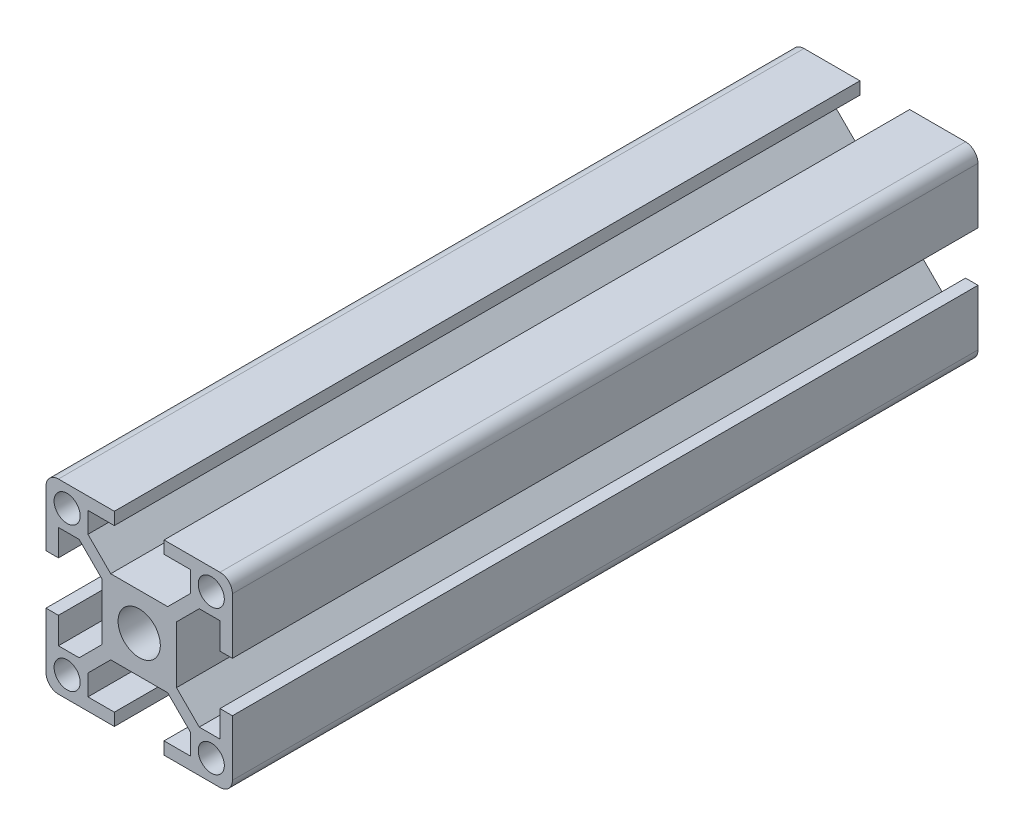
SolidWorks part; units mm, degrees
material "6063-O, Extruded Rod (SS)"
ref_plane "Front Plane" through (0, 0, 0) normal (0, 0, 1) x (1, 0, 0)
ref_plane "Top Plane" through (0, 0, 0) normal (0, 1, 0) x (1, 0, 0)
ref_plane "Right Plane" through (0, 0, 0) normal (1, 0, 0) x (0, 0, -1)
sketch "Sketch1" plane through (0, 0, 0) normal (0, 0, 1) x (1, 0, 0)
  line L0 (-4, 15) -> (-4, -15) construction
  line L1 (15, -15) -> (4, -15)
  line L2 (15, -15) -> (15, -4)
  line L3 (15, 15) -> (4, 15)
  line L4 (-15, -15) -> (-15, -4)
  line L5 (15, -15) -> (-15, 15) construction
  line L6 (15, 15) -> (-15, -15) construction
  line L7 (0, 15) -> (0, -15) construction
  line L8 (4, 15) -> (4, -15) construction
  line L9 (-8.25, 15) -> (-8.25, -15) construction
  line L10 (8.25, 15) -> (8.25, -15) construction
  line L11 (8.25, 13) -> (8.25, 9.6642)
  line L12 (4.5858, -6) -> (-4.5858, -6)
  line L13 (6, -4.5858) -> (6, 4.5858)
  line L14 (4.5858, 6) -> (-4.5858, 6)
  line L15 (-6, -4.5858) -> (-6, 4.5858)
  line L16 (6, -6) -> (-6, 6) construction
  line L17 (6, 6) -> (-6, -6) construction
  line L20 (-13, 8.25) -> (-9.6642, 8.25)
  line L21 (-8.25, 13) -> (-8.25, 9.6642)
  line L22 (-14.95, 14.95) -> (-8.25, 8.25) construction
  line L23 (-14.95, 8.25) -> (-8.25, 14.95) construction
  line L24 (-10.2, 13) -> (-10.0348, 13)
  line L25 (-13, 10.2) -> (-13, 10.0348)
  line L26 (-8.25, -13) -> (-4, -13)
  line L27 (13, 8.25) -> (13, 4)
  line L28 (-13, 13) -> (13, -13) construction
  line L29 (-13, -13) -> (13, 13) construction
  line L30 (13, 8.25) -> (9.6642, 8.25)
  line L31 (13, -8.25) -> (9.6642, -8.25)
  line L32 (8.25, -13) -> (8.25, -9.6642)
  line L33 (-8.25, -13) -> (-8.25, -9.6642)
  line L34 (-13, -8.25) -> (-9.6642, -8.25)
  line L35 (-8.25, 8.25) -> (-6, 6)
  line L36 (-9.6642, 8.25) -> (-6, 4.5858)
  line L37 (-8.25, 9.6642) -> (-4.5858, 6)
  line L38 (-8.9571, 7.5429) -> (-6.7071, 5.2929) construction
  line L39 (-7.5429, 8.9571) -> (-5.2929, 6.7071) construction
  line L40 (-4, 15) -> (-4, 13)
  line L41 (4, 15) -> (4, 13)
  line L42 (8.25, 9.6642) -> (4.5858, 6)
  line L43 (9.6642, 8.25) -> (6, 4.5858)
  line L44 (15, 4) -> (13, 4)
  line L45 (15, -4) -> (13, -4)
  line L46 (9.6642, -8.25) -> (6, -4.5858)
  line L47 (8.25, -9.6642) -> (4.5858, -6)
  line L48 (4, -15) -> (4, -13)
  line L49 (-4, -15) -> (-4, -13)
  line L50 (-8.25, -9.6642) -> (-4.5858, -6)
  line L51 (-9.6642, -8.25) -> (-6, -4.5858)
  line L52 (-15, -4) -> (-13, -4)
  line L53 (-15, 4) -> (-13, 4)
  line L54 (-15, 4) -> (-15, 15)
  line L55 (-13, -4) -> (-13, -8.25)
  line L56 (4, 13) -> (8.25, 13)
  line L57 (-4, 15) -> (-15, 15)
  line L58 (13, -4) -> (13, -8.25)
  line L59 (15, 4) -> (15, 15)
  line L60 (-8.25, 13) -> (-4, 13)
  line L61 (-13, 8.25) -> (-13, 4)
  line L62 (4, -13) -> (8.25, -13)
  line L63 (-4, -15) -> (-15, -15)
  circle A0 centre (0, 0) radius 3.4
  circle A1 centre (-11.6, 11.6) radius 2.1
  circle A2 centre (11.6, 11.6) radius 2.1
  circle A3 centre (11.6, -11.6) radius 2.1
  circle A4 centre (-11.6, -11.6) radius 2.1
  point P0 (0, 0)
  point P19 (-11.6, 15)
  point P52 (0, 0)
  point P87 (0, 0)
  dimension "D3" = 6.8
  dimension "D9" = 4.2
  dimension "D1" = 30
  dimension "D2" = 30
  dimension "D4" = 11
  dimension "D5" = 8.25
  dimension "D6" = 11.6
  dimension "D7" = 3.4
  dimension "D8" = 3.4
  dimension "D10" = 12
  dimension "D11" = 2
  dimension "D13" = 1
  dimension "D14" = 1
  dimension "D12" = 4
  dimension "D15" = 4
extrude "Boss-Extrude1" add sketch "Sketch1" along normal blind 120
fillet "Fillet1" radius 2 4 edges at (-15, -15, 60) (15, -15, 60) (-15, 15, 60) (15, 15, 60)
ref_plane "Plane1" through (0, 0, 0) normal (1, 0, 0) x (0, 0, -1)
